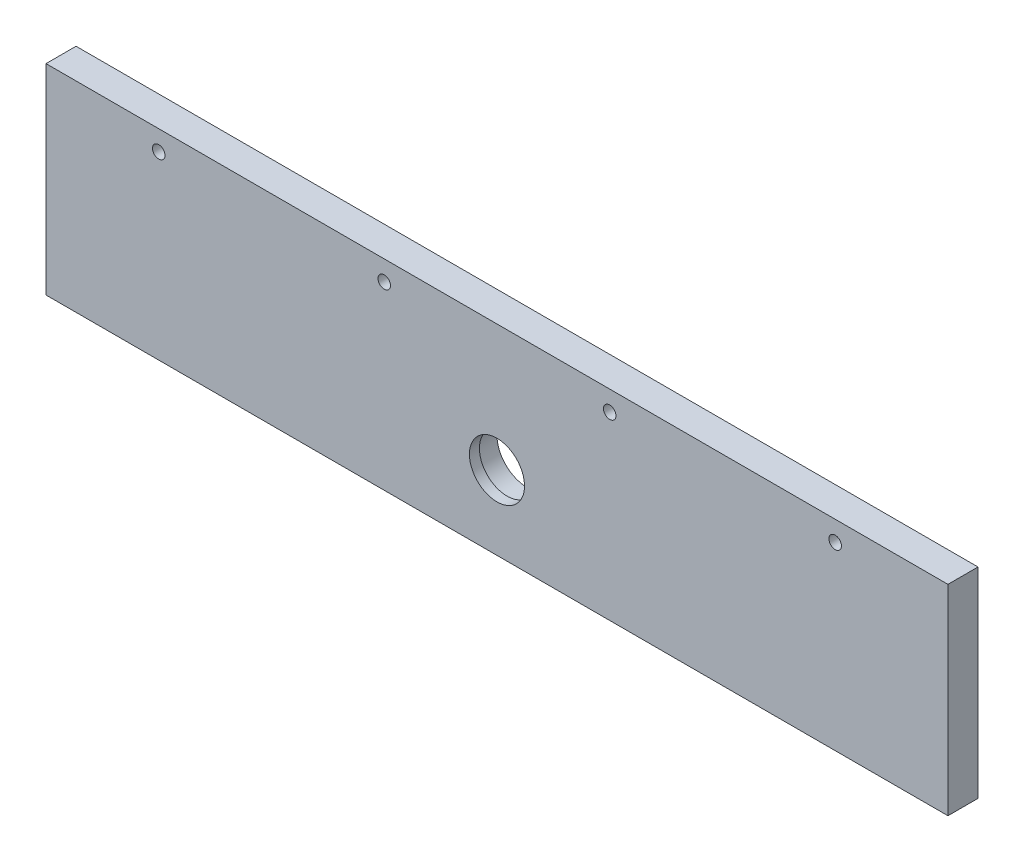
SolidWorks part; units mm, degrees
material "HDPE-green"
ref_plane "Front Plane" through (0, 0, 0) normal (0, 0, 1) x (1, 0, 0)
ref_plane "Top Plane" through (0, 0, 0) normal (0, 1, 0) x (1, 0, 0)
ref_plane "Right Plane" through (0, 0, 0) normal (1, 0, 0) x (0, 0, -1)
sketch "Sketch1" plane through (0, 0, 0) normal (0, 0, 1) x (1, 0, 0)
  line L1 (-180, -40) -> (180, -40)
  line L2 (-180, -40) -> (-180, 40)
  line L3 (-180, 40) -> (180, 40)
  line L4 (180, -40) -> (180, 40)
  line L5 (-180, -40) -> (180, 40) construction
  line L6 (-180, 40) -> (180, -40) construction
  point P0 (0, 0)
extrude "Boss-Extrude1" add sketch "Sketch1" along normal blind 12
sketch "Sketch2" plane through (0, 0, 12) normal (0, 0, 1) x (1, 0, 0)
  line L0 (-180, 40) -> (-180, -40) construction
  line L1 (180, 40) -> (-180, 40) construction
  circle A0 centre (-135, 32) radius 2.5
  dimension "D1" = 5
  dimension "D2" = 45
  dimension "D3" = 8
extrude "Cut-Extrude1" cut sketch "Sketch2" against normal up to next
sketch "Sketch4" plane through (-23.3914, 111.1762, 0) normal (0, 0, -1) x (-1, 0, 0)
  line L0 (107.6086, -139.1762) -> (115.6086, -139.1762) construction
  line L1 (107.6086, -137.1762) -> (115.6086, -137.1762)
  line L2 (107.6086, -141.1762) -> (115.6086, -141.1762)
  line L3 (156.6086, -151.1762) -> (-203.3914, -151.1762) construction
  arc A0 (107.6086, -137.1762) -> (107.6086, -141.1762) centre (107.6086, -139.1762) ccw
  arc A1 (115.6086, -141.1762) -> (115.6086, -137.1762) centre (115.6086, -139.1762) ccw
  point P2 (111.6086, -139.1762)
  dimension "D1" = 8
  dimension "D2" = 2
  dimension "D4" = 12
  dimension "D3" = 135
extrude "Cut-Extrude2" cut sketch "Sketch4" against normal blind 8
sketch "Sketch6" plane through (-23.3914, 111.1762, 0) normal (0, 0, -1) x (-1, 0, 0)
  line L0 (111.6086, -134.1762) -> (111.6086, -164.83) construction
  line L1 (114.1086, -134.1762) -> (114.1086, -164.83)
  line L2 (109.1086, -134.1762) -> (109.1086, -164.83)
  line L4 (156.6086, -71.1762) -> (156.6086, -151.1762) construction
  line L6 (156.6086, -151.1762) -> (-203.3914, -151.1762) construction
  arc A0 (114.1086, -134.1762) -> (109.1086, -134.1762) centre (111.6086, -134.1762) ccw
  arc A1 (109.1086, -164.83) -> (114.1086, -164.83) centre (111.6086, -164.83) ccw
  point P2 (111.6086, -149.5031)
  dimension "D1" = 135
  dimension "D2" = 2.5
  dimension "D3" = 17
extrude "Cut-Extrude3" cut sketch "Sketch6" against normal blind 6.5
pattern_linear "LPattern1" count 4 spacing 90 along (1, 0, 0) of "Cut-Extrude1", "Cut-Extrude2", "Cut-Extrude3"
sketch "Sketch7" plane through (0, 0, 0) normal (0, 0, -1) x (-1, 0, 0)
  line L0 (42.5, -40) -> (-42.5, -40) construction
  circle A0 centre (0, -10.5) radius 12
  dimension "D1" = 29.5
  dimension "D2" = 24
extrude "Cut-Extrude4" cut sketch "Sketch7" against normal blind 8
sketch "Sketch8" plane through (0, 0, 8) normal (0, 0, -1) x (-1, 0, 0)
  circle A0 centre (0, -10.5) radius 11
  dimension "D1" = 22
extrude "Cut-Extrude5" cut sketch "Sketch8" against normal up to next
